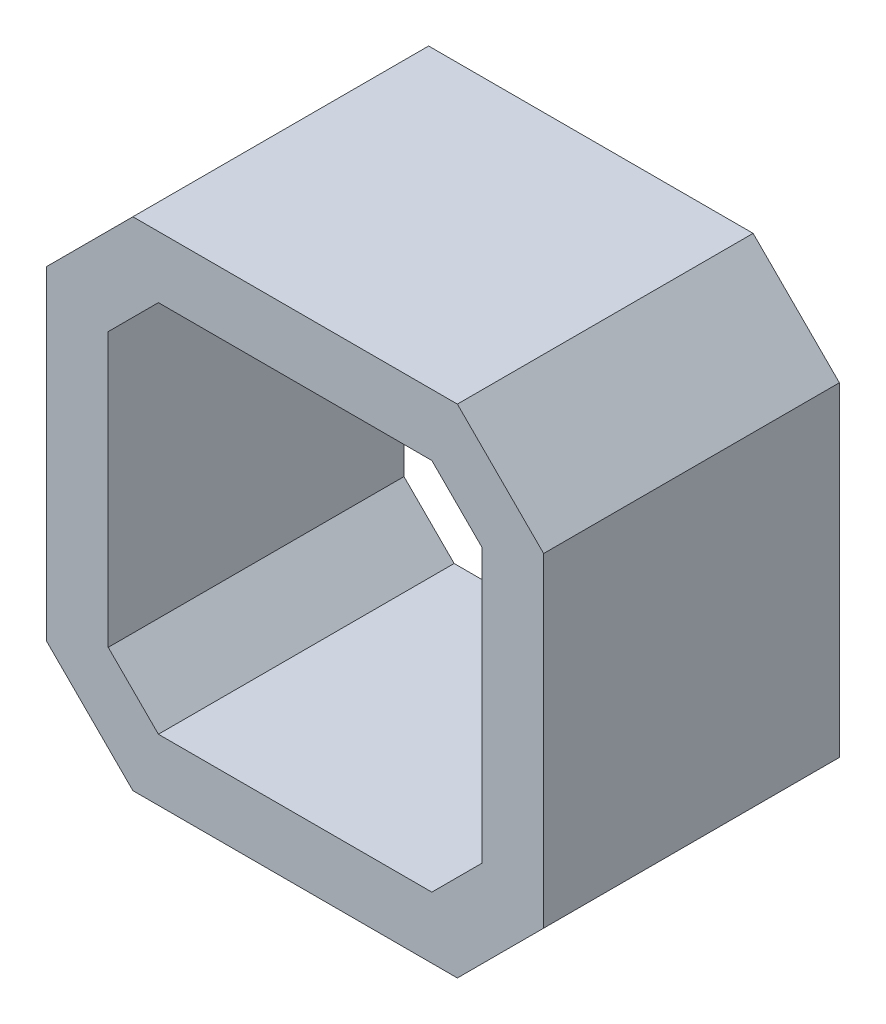
SolidWorks part; units mm, degrees
ref_plane "Front Plane" through (0, 0, 0) normal (0, 0, 1) x (1, 0, 0)
ref_plane "Top Plane" through (0, 0, 0) normal (0, 1, 0) x (1, 0, 0)
ref_plane "Right Plane" through (0, 0, 0) normal (1, 0, 0) x (0, 0, -1)
sketch "Sketch1" plane through (0, 0, 0) normal (0, 0, 1) x (1, 0, 0)
  line L0 (-39.5, 60.5) -> (-60.5, 39.5)
  line L1 (39.5, -60.5) -> (-39.5, -60.5)
  line L2 (60.5, -39.5) -> (60.5, 39.5)
  line L3 (39.5, 60.5) -> (-39.5, 60.5)
  line L4 (-60.5, -39.5) -> (-60.5, 39.5)
  line L5 (60.5, -60.5) -> (-60.5, 60.5) construction
  line L6 (60.5, 60.5) -> (-60.5, -60.5) construction
  line L7 (60.5, 39.5) -> (39.5, 60.5)
  line L8 (60.5, -39.5) -> (39.5, -60.5)
  line L9 (-39.5, -60.5) -> (-60.5, -39.5)
  line L10 (33.2868, 45.5) -> (-33.2868, 45.5)
  line L11 (-33.2868, 45.5) -> (-45.5, 33.2868)
  line L12 (-45.5, -33.2868) -> (-45.5, 33.2868)
  line L13 (-33.2868, -45.5) -> (-45.5, -33.2868)
  line L14 (33.2868, -45.5) -> (-33.2868, -45.5)
  line L15 (45.5, -33.2868) -> (33.2868, -45.5)
  line L16 (45.5, -33.2868) -> (45.5, 33.2868)
  line L17 (45.5, 33.2868) -> (33.2868, 45.5)
  point P0 (0, 0)
  dimension "D1" = 121
  dimension "D2" = 121
  dimension "D3" = 15
extrude "Boss-Extrude1" add sketch "Sketch1" along normal blind 72
scale "Escala2" scale about centroid uniform scaling yes scale factor 0.5
